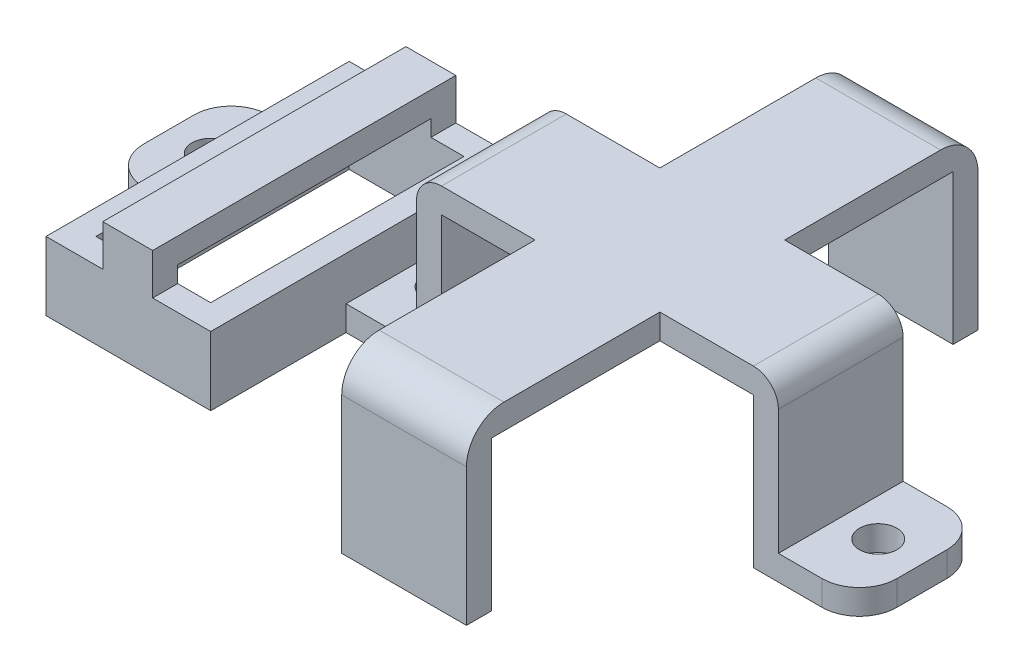
SolidWorks part; units mm, degrees
ref_plane "Alzado" through (0, 0, 0) normal (0, 0, 1) x (1, 0, 0)
ref_plane "Planta" through (0, 0, 0) normal (0, 1, 0) x (1, 0, 0)
ref_plane "Vista lateral" through (0, 0, 0) normal (1, 0, 0) x (0, 0, -1)
sketch "Croquis1" plane through (0, 0, 0) normal (0, 0, 1) x (1, 0, 0)
  line L0 (0, 0) -> (7.5, 0)
  line L5 (7.5, 0) -> (7.5, 12)
  line L6 (7.5, 12) -> (32.5, 12)
  line L7 (40, 0) -> (41, 0)
  line L8 (32.5, 0) -> (32.5, 12)
  line L9 (0, 0) -> (-2.15, 0)
  line L10 (20, 12) -> (20, 0) construction
  line L11 (40, 0) -> (32.5, 0)
  dimension "D1" = 25
  dimension "D2" = 7.5
  dimension "D3" = 1
  dimension "D5" = 2.15
  dimension "D6" = 12
extrude "Extruir-Lámina1" add sketch "Croquis1" against normal blind 10 thin thin type one direction reverse wall 2
fillet "Redondeo3" radius 2 2 edges at (5.5, 14, -5) (34.5, 14, -5)
ref_plane "Plano1" through (20, 0, 0) normal (1, 0, 0) x (0, 0, -1)
sketch "Croquis2" plane through (0, 2, 0) normal (0, 1, 0) x (1, 0, 0)
  line L0 (-2.15, 5) -> (39, 5) construction
  line L1 (-2.15, 10) -> (-2.15, 0) construction
  line L3 (7.5, 10) -> (7.5, 0) construction
  line L4 (7.5, 10) -> (7.5, 0) construction
  circle A0 centre (2.5, 5) radius 1.5
  circle A1 centre (37.5, 5) radius 1.5
  dimension "D1" = 3
  dimension "D2" = 5
  dimension "D3" = 35
sketch "Croquis3" plane through (20, 0, 0) normal (1, 0, 0) x (0, 0, -1)
  line L0 (0, 14) -> (10, 14) construction
  line L1 (0, 14) -> (10, 14) construction
  line L2 (23.5, 12) -> (-13.5, 12)
  line L3 (23.5, 12) -> (23.5, 0)
  line L5 (5, 12) -> (5, 14) construction
  line L7 (-13.5, 12) -> (-13.5, 0)
  dimension "D1" = 12
  dimension "D2" = 18.5
extrude "Extruir-Lámina2" add sketch "Croquis3" along normal mid plane 10 thin
fillet "Redondeo4" radius 3 2 edges at (20, 14, -25.5) (20, 14, 15.5)
extrude "Cortar-Extruir1" cut sketch "Croquis2" against normal blind 10
sketch "Croquis5" plane through (0, 2, 0) normal (0, 1, 0) x (1, 0, 0)
  line L0 (-2.15, 10) -> (-2.15, 0) construction
  line L1 (-2.15, 10) -> (-2.15, 0) construction
  line L2 (-2.15, 1.3) -> (-11.35, 1.3) construction
  line L3 (-2.15, 11.45) -> (-11.35, 11.45)
  line L4 (-2.15, 11.45) -> (-2.15, -8.85)
  line L5 (-2.15, -8.85) -> (-11.35, -8.85)
  line L6 (-11.35, 11.45) -> (-11.35, -8.85)
  line L7 (1, 5) -> (-2.15, 5) construction
  circle A0 centre (2.5, 5) radius 1.5 construction
  dimension "D1" = 9.2
  dimension "D2" = 20.3
  dimension "D3" = 3.7
extrude "Extruir-Lámina3" add sketch "Croquis5" along normal blind 3.5 and the other way up to surface thin
sketch "Croquis7" plane through (-13.35, 0, 0) normal (-1, 0, 0) x (0, 0, 1)
  line L0 (0, 2) -> (0, 0) construction
  line L1 (-10, 2) -> (-10, 0) construction
  line L2 (-10, 2) -> (0, 2) construction
  line L3 (0, 2) -> (0, 0)
  line L4 (-10, 2) -> (-10, 0)
  line L5 (-10, 2) -> (0, 2)
  line L6 (-10, 0) -> (0, 0)
extrude "Saliente-Extruir1" add sketch "Croquis7" along normal blind 6
sketch "Croquis8" plane through (0, 2, 0) normal (0, 1, 0) x (1, 0, 0)
  line L0 (1, 5) -> (-19.35, 5) construction
  line L1 (-19.35, 0) -> (-19.35, 10) construction
  circle A0 centre (2.5, 5) radius 1.5 construction
  circle A1 centre (-16, 5) radius 1.5
  circle A2 centre (2.5, 5) radius 1.5 construction
  dimension "D1" = 18.5
extrude "Cortar-Extruir2" cut sketch "Croquis8" against normal through all both and the other way through all
ref_plane "Plano3" through (-6.8, 0, 0) normal (-1, 0, 0) x (0, 0, 1)
sketch "Croquis9" plane through (-6.8, 0, 0) normal (-1, 0, 0) x (0, 0, 1)
  line L0 (8.85, 5.5) -> (-11.45, 5.5) construction
  line L1 (8.85, 5.5) -> (-11.45, 5.5) construction
  line L2 (8.85, 5.5) -> (8.85, 6.8)
  line L3 (8.85, 6.8) -> (-11.45, 6.8)
  line L4 (-11.45, 6.8) -> (-11.45, 5.5)
  dimension "D1" = 1.3
extrude "Extruir-Lámina4" add sketch "Croquis9" along normal mid plane 4 thin
fillet "Redondeo5" radius 3 4 edges at (41, 1, -10) (41, 1, 0) (-19.35, 1, -10) (-19.35, 1, 0)
